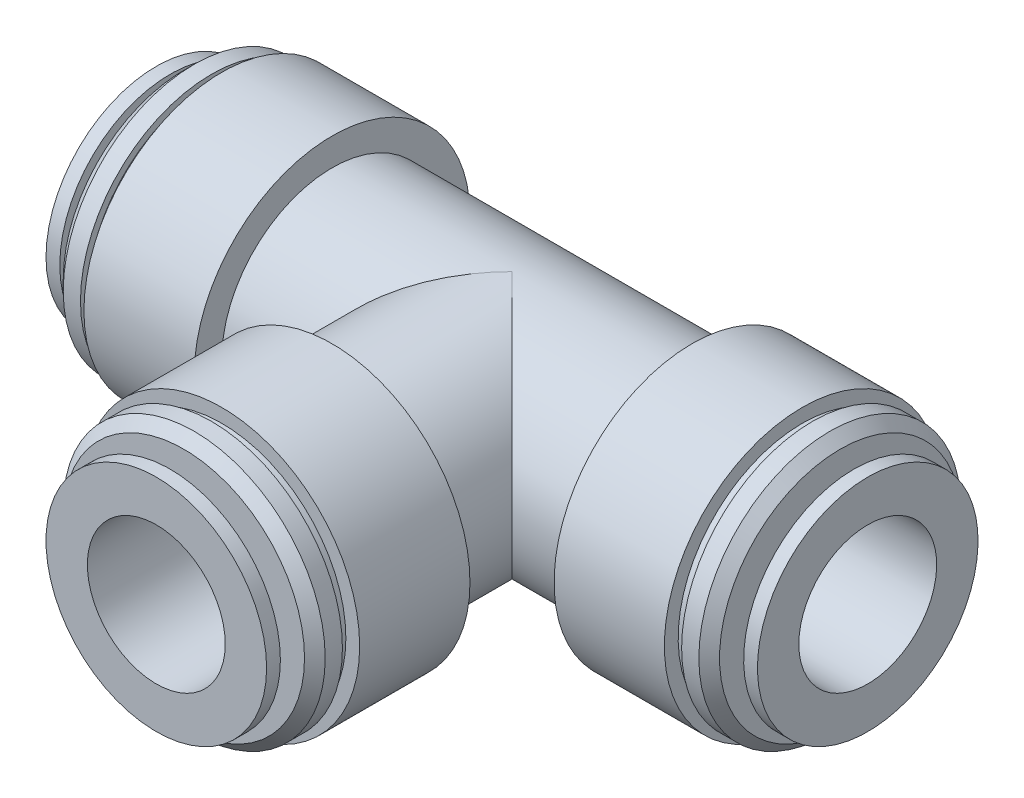
SolidWorks part; units mm, degrees
ref_plane "Спереди" through (0, 0, 0) normal (0, 0, 1) x (1, 0, 0)
ref_plane "Сверху" through (0, 0, 0) normal (0, 1, 0) x (1, 0, 0)
ref_plane "Справа" through (0, 0, 0) normal (1, 0, 0) x (0, 0, -1)
sketch "Эскиз1" plane through (0, 0, 0) normal (0, 0, 1) x (1, 0, 0)
  line L0 (-16.75, -8) -> (-16.75, -6)
  line L1 (-17.75, -4) -> (-17.75, -8)
  line L2 (-13, -9) -> (-13, -10)
  line L3 (-17.75, -8) -> (-16.75, -8)
  line L4 (-15.75, -6) -> (-15.75, -8.75)
  line L5 (-15, -9.5) -> (-13.75, -9.5)
  line L6 (-15.75, -8.75) -> (-15, -9.5)
  line L7 (-13.75, -9.5) -> (-13.75, -9)
  line L8 (-13.75, -9) -> (-13, -9)
  line L9 (-17.75, -4) -> (-5, -4)
  line L10 (-16.75, -6) -> (-15.75, -6)
  line L11 (-13, -10) -> (-5, -10)
  line L12 (-5, -10) -> (-5, -4)
  line L13 (-21.0495, 0) -> (4.2526, 0) construction
  point P5 (-15.75, -9.5)
  dimension "D1" = 0.75
  dimension "D2" = 0.75
revolve "Повернуть1" add sketch "Эскиз1" angle 360 about L13
sketch "Эскиз2" plane through (-5, 0, 0) normal (1, 0, 0) x (0, 0, -1)
  circle A0 centre (0, 0) radius 8
  circle A1 centre (0, 0) radius 4
extrude "Бобышка-Вытянуть1" add sketch "Эскиз2" along normal blind 26.1
sketch "Эскиз3" plane through (0, 0, 0) normal (0, 0, 1) x (1, 0, 0)
  line L0 (32.85, 8) -> (32.85, 6)
  line L1 (33.85, 4) -> (33.85, 8)
  line L2 (29.1, 9) -> (29.1, 10)
  line L3 (33.85, 8) -> (32.85, 8)
  line L4 (31.85, 6) -> (31.85, 8.75)
  line L5 (31.1, 9.5) -> (29.85, 9.5)
  line L6 (31.85, 8.75) -> (31.1, 9.5)
  line L7 (29.85, 9.5) -> (29.85, 9)
  line L8 (29.85, 9) -> (29.1, 9)
  line L9 (33.85, 4) -> (21.1, 4)
  line L10 (32.85, 6) -> (31.85, 6)
  line L11 (29.1, 10) -> (21.1, 10)
  line L12 (21.1, 10) -> (21.1, 4)
  line L13 (47.1495, 0) -> (14.4859, 0) construction
  line L14 (21.1, -8) -> (21.1, 8) construction
  point P5 (31.85, 9.5)
  dimension "D1" = 0.75
  dimension "D2" = 0.75
  dimension "D3" = 0.75
  dimension "D4" = 2.75
  dimension "D5" = 1.25
  dimension "D6" = 1
  dimension "D7" = 1
revolve "Повернуть2" add sketch "Эскиз3" angle 360 about L13
sketch "Эскиз4" plane through (0, 0, 0) normal (0, 0, 1) x (1, 0, 0)
  circle A0 centre (8.05, 0) radius 8
extrude "Бобышка-Вытянуть2" add sketch "Эскиз4" along normal blind 13.05
sketch "Эскиз5" plane through (0, 0, 0) normal (0, 1, 0) x (1, 0, 0)
  line L0 (16.05, -24.8) -> (14.05, -24.8)
  line L1 (12.05, -25.8) -> (16.05, -25.8)
  line L2 (17.05, -21.05) -> (18.05, -21.05)
  line L3 (16.05, -25.8) -> (16.05, -24.8)
  line L4 (14.05, -23.8) -> (16.8, -23.8)
  line L5 (17.55, -23.05) -> (17.55, -21.8)
  line L6 (16.8, -23.8) -> (17.55, -23.05)
  line L7 (17.55, -21.8) -> (17.05, -21.8)
  line L8 (17.05, -21.8) -> (17.05, -21.05)
  line L9 (12.05, -25.8) -> (12.05, -13.05)
  line L10 (14.05, -24.8) -> (14.05, -23.8)
  line L11 (18.05, -21.05) -> (18.05, -13.05)
  line L12 (18.05, -13.05) -> (12.05, -13.05)
  line L13 (8.05, -29.0995) -> (8.05, -3.7974) construction
  point P5 (17.55, -23.8)
  dimension "D1" = 0.75
  dimension "D2" = 0.75
revolve "Повернуть3" add sketch "Эскиз5" angle 360 about L13
sketch "Эскиз6" plane through (-17.75, 0, 0) normal (-1, 0, 0) x (0, 0, 1)
  circle A0 centre (0, 0) radius 5
  dimension "D1" = 10
extrude "Вырез-Вытянуть1" cut sketch "Эскиз6" against normal blind 63.05
sketch "Эскиз7" plane through (0, 0, 25.8) normal (0, 0, 1) x (1, 0, 0)
  circle A0 centre (8.05, 0) radius 5
  dimension "D1" = 10
extrude "Вырез-Вытянуть2" cut sketch "Эскиз7" against normal blind 25
